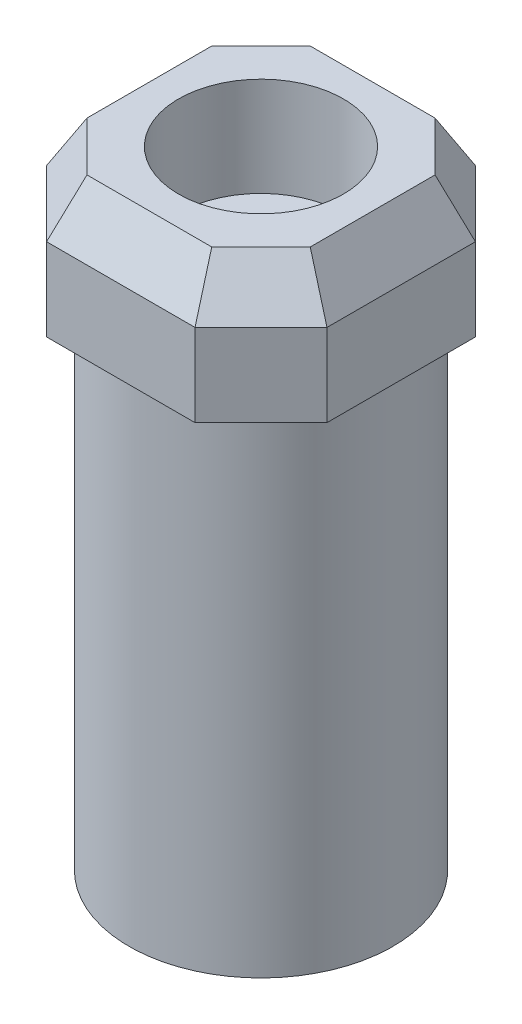
SolidWorks part; units mm, degrees
ref_plane "Front Plane" through (0, 0, 0) normal (0, 0, 1) x (1, 0, 0)
ref_plane "Top Plane" through (0, 0, 0) normal (0, 1, 0) x (1, 0, 0)
ref_plane "Right Plane" through (0, 0, 0) normal (1, 0, 0) x (0, 0, -1)
sketch "Sketch1" plane through (0, 0, 0) normal (0, 1, 0) x (1, 0, 0)
  line L1 (-8.5, 8.5) -> (8.5, 8.5)
  line L2 (-8.5, 8.5) -> (-8.5, -8.5)
  line L3 (-8.5, -8.5) -> (8.5, -8.5)
  line L4 (8.5, 8.5) -> (8.5, -8.5)
  line L5 (0, -8.5) -> (0, 8.5) construction
  line L6 (-8.5, 0) -> (8.5, 0) construction
  point P0 (0, 0)
  dimension "D1" = 17
extrude "Boss-Extrude1" add sketch "Sketch1" along normal blind 8
sketch "Sketch5" plane through (0, 0, 0) normal (0, -1, 0) x (1, 0, 0)
  circle A0 centre (0, 0) radius 8
  dimension "D1" = 16
extrude "Boss-Extrude3" add sketch "Sketch5" along normal blind 30
sketch "Sketch6" plane through (0, -30, 0) normal (0, -1, 0) x (1, 0, 0)
  circle A0 centre (0, 0) radius 6
  dimension "D1" = 12
extrude "Cut-Extrude5" cut sketch "Sketch6" against normal up to vertex (30 mm away)
sketch "Sketch8" plane through (0, 0, 0) normal (1, 0, 0) x (0, 0, -1)
  line L0 (0, 9.35) -> (0, -9.35) construction
  line L1 (-1.4, -20) -> (1.4, -20) construction
  line L2 (-1.4, -20) -> (-1.4, -10)
  line L3 (-1.4, -10) -> (1.4, -10) construction
  line L4 (1.4, -20) -> (1.4, -10)
  line L5 (0, -10) -> (0, -20) construction
  line L6 (-1.4, -15) -> (1.4, -15) construction
  line L7 (-8, -30) -> (8, -30) construction
  arc A0 (-1.4, -20) -> (1.4, -20) centre (0, -20) ccw
  arc A1 (1.4, -10) -> (-1.4, -10) centre (0, -10) ccw
  point P0 (0, -15)
  dimension "D1" = 10
  dimension "D2" = 10
  dimension "D3" = 2.8
extrude "Cut-Extrude6" cut sketch "Sketch8" against normal through all
chamfer "Chamfer1" distance 4 angle 45 4 edges at (-8.5, 4, 8.5) (8.5, 4, 8.5) (-8.5, 4, -8.5) (8.5, 4, -8.5)
sketch "Sketch11" plane through (0, 8, 0) normal (0, 1, 0) x (1, 0, 0)
  circle A0 centre (0, 0) radius 5
  dimension "D1" = 10
extrude "Cut-Extrude7" cut sketch "Sketch11" against normal blind 6
chamfer "Chamfer2" distance 3 angle 30 8 edges at (-6.5, 8, 6.5) (-8.5, 8, 0) (-6.5, 8, -6.5) (0, 8, -8.5) (6.5, 8, -6.5) (8.5, 8, 0) (6.5, 8, 6.5) (0, 8, 8.5)
